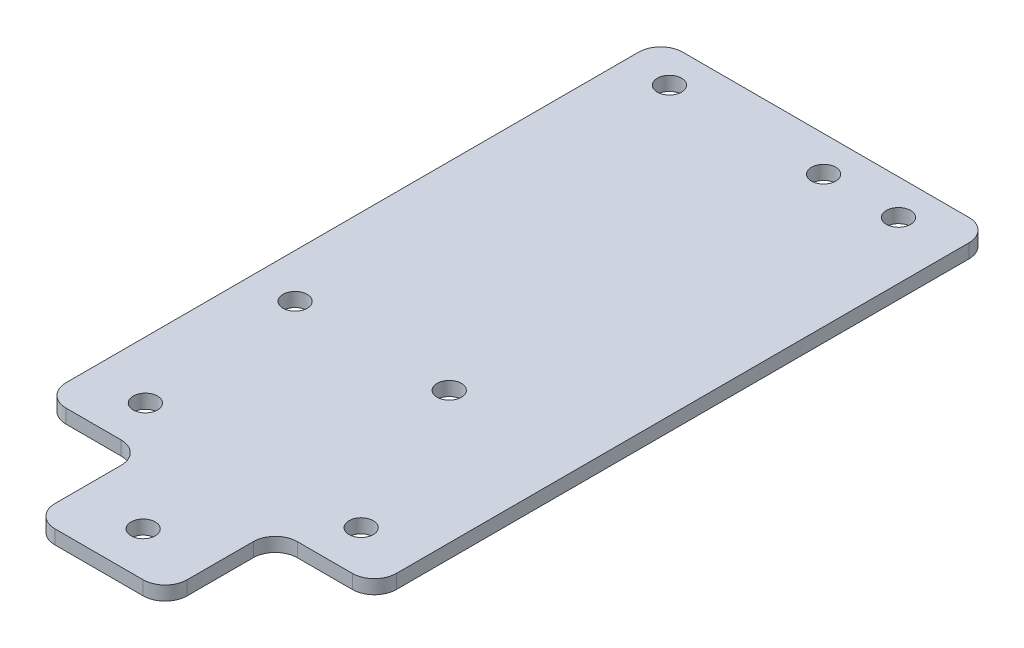
SolidWorks part; units mm, degrees
ref_plane "Front Plane" through (0, 0, 0) normal (0, 0, 1) x (1, 0, 0)
ref_plane "Top Plane" through (0, 0, 0) normal (0, 1, 0) x (1, 0, 0)
ref_plane "Right Plane" through (0, 0, 0) normal (1, 0, 0) x (0, 0, -1)
sketch "Sketch3" plane through (0, 0, 0) normal (0, 1, 0) x (1, 0, 0)
  line L0 (10, -8) -> (62, -8) construction
  line L1 (5, 0) -> (70, 0)
  line L2 (0, -5) -> (0, -135)
  line L3 (5, -140) -> (17.5, -140)
  line L4 (75, -5) -> (75, -135)
  line L5 (10, -50.5) -> (40.2583, -50.5) construction
  line L6 (57.5, -140) -> (70, -140)
  line L8 (22.5, -145) -> (22.5, -160)
  line L9 (27.5, -165) -> (47.5, -165)
  line L10 (52.5, -145) -> (52.5, -160)
  circle A0 centre (10, -8) radius 2.75
  circle A1 centre (45, -8) radius 2.75
  circle A2 centre (62, -8) radius 2.75
  circle A4 centre (45, -93) radius 2.75
  circle A5 centre (10, -93) radius 2.75
  arc A6 (70, -140) -> (75, -135) centre (70, -135) ccw
  arc A7 (0, -135) -> (5, -140) centre (5, -135) ccw
  arc A8 (70, 0) -> (75, -5) centre (70, -5) cw
  arc A9 (5, 0) -> (0, -5) centre (5, -5) ccw
  arc A10 (17.5, -140) -> (22.5, -145) centre (17.5, -145) cw
  arc A11 (57.5, -140) -> (52.5, -145) centre (57.5, -145) ccw
  arc A12 (47.5, -165) -> (52.5, -160) centre (47.5, -160) ccw
  arc A13 (22.5, -160) -> (27.5, -165) centre (27.5, -160) ccw
  circle A14 centre (37.5, -155) radius 2.75
  circle A15 centre (62, -130) radius 2.75
  circle A16 centre (13, -130) radius 2.75
  point P21 (0, -140)
  point P24 (75, 0)
  point P27 (0, 0)
  point P38 (52.5, -165)
  point P41 (22.5, -165)
  dimension "D3" = 5.5
  dimension "D4" = 5.5
  dimension "D5" = 5.5
  dimension "D9" = 5
  dimension "D14" = 5
  dimension "D16" = 5.5
  dimension "D19" = 5.5
  dimension "D22" = 5.5
  dimension "D1" = 140
  dimension "D2" = 75
  dimension "D6" = 35
  dimension "D7" = 17
  dimension "D8" = 42.5
  dimension "D10" = 8
  dimension "D11" = 10
  dimension "D12" = 30
  dimension "D13" = 22.5
  dimension "D15" = 25
  dimension "D17" = 10
  dimension "D18" = 15
  dimension "D20" = 13
  dimension "D21" = 10
  dimension "D23" = 13
  dimension "D24" = 10
extrude "Boss-Extrude2" add sketch "Sketch3" along normal blind 3.175
